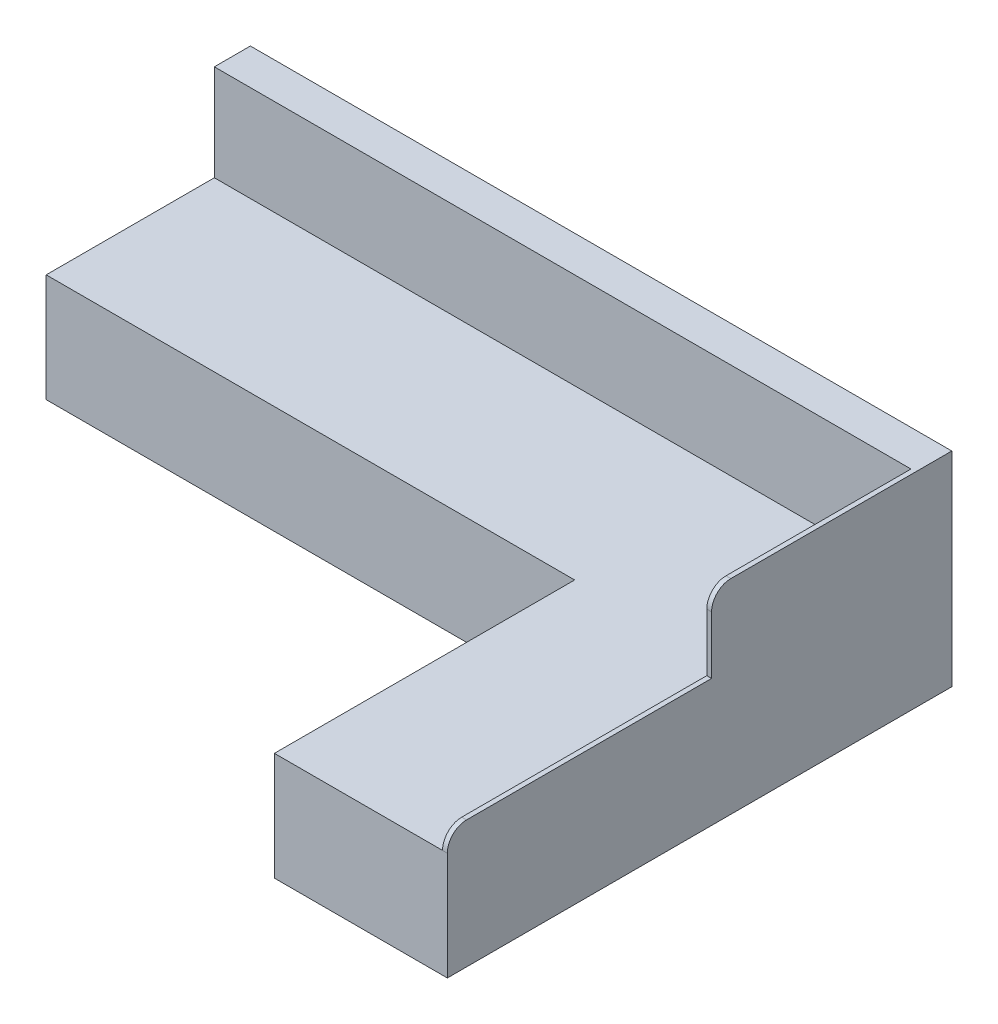
SolidWorks part; units mm, degrees
ref_plane "Front Plane" through (0, 0, 0) normal (0, 0, 1) x (1, 0, 0)
ref_plane "Top Plane" through (0, 0, 0) normal (0, 1, 0) x (1, 0, 0)
ref_plane "Right Plane" through (0, 0, 0) normal (1, 0, 0) x (0, 0, -1)
sketch "Sketch1" plane through (0, 0, 0) normal (0, 1, 0) x (1, 0, 0)
  line L0 (750, -425) -> (750, -1675)
  line L1 (750, -425) -> (-1450, -425)
  line L4 (-1450, -425) -> (-1450, 425)
  line L5 (1450, 425) -> (-1450, 425)
  line L8 (1450, 425) -> (1450, -1675)
  line L9 (1450, -1675) -> (750, -1675)
  dimension "D1" = 2900
  dimension "D2" = 850
  dimension "D3" = 700
  dimension "D4" = 2100
extrude "Boss-Extrude1" add sketch "Sketch1" along normal blind 450
sketch "Sketch3" plane through (0, 450, 0) normal (0, 1, 0) x (1, 0, 0)
  line L0 (1450, -1675) -> (1450, 425) construction
  line L1 (-1450, 425) -> (1450, 425)
  line L2 (-1450, 425) -> (-1450, 275)
  line L3 (-1450, 275) -> (1450, 275)
  line L4 (1450, 425) -> (1450, 275)
  dimension "D1" = 150
extrude "Boss-Extrude3" add sketch "Sketch3" along normal blind 400
sketch "Sketch5" plane through (1450, 0, 0) normal (1, 0, 0) x (0, 0, -1)
  line L0 (-575, 770) -> (-575, 530)
  line L1 (-1675, 0) -> (425, 0)
  line L2 (-1675, 0) -> (-1675, 450)
  line L3 (-495, 850) -> (425, 850)
  line L4 (425, 0) -> (425, 850)
  line L5 (-575, 530) -> (-1595, 530)
  arc A0 (-495, 850) -> (-575, 770) centre (-495, 770) ccw
  arc A1 (-1595, 530) -> (-1675, 450) centre (-1595, 450) ccw
  dimension "D3" = 80
  dimension "D1" = 1000
  dimension "D2" = 530
extrude "Boss-Extrude4" add sketch "Sketch5" along normal blind 20
